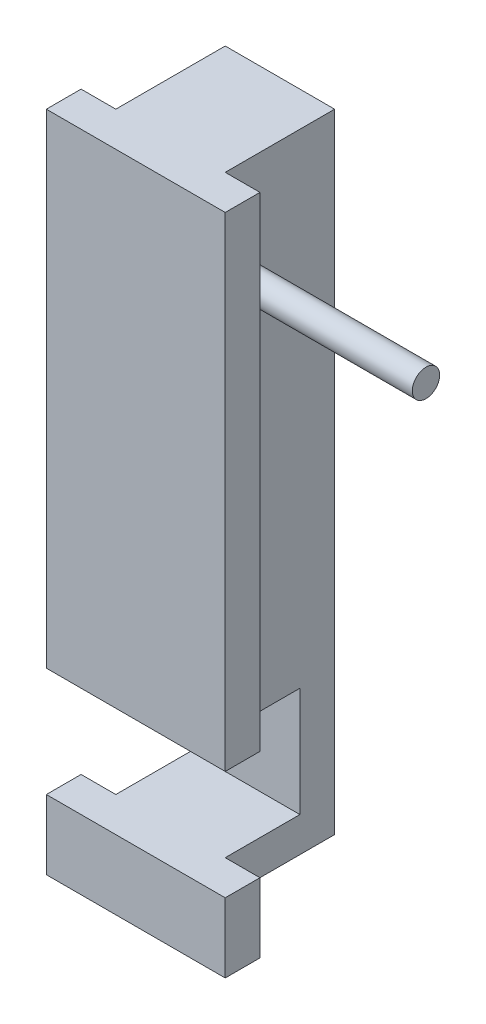
SolidWorks part; units mm, degrees
ref_plane "Front Plane" through (0, 0, 0) normal (0, 0, 1) x (1, 0, 0)
ref_plane "Top Plane" through (0, 0, 0) normal (0, 1, 0) x (1, 0, 0)
ref_plane "Right Plane" through (0, 0, 0) normal (1, 0, 0) x (0, 0, -1)
sketch "Sketch2" plane through (0, 0, 0) normal (1, 0, 0) x (0, 0, -1)
  line L0 (0, 0) -> (20, 0)
  line L1 (20, 0) -> (20, -20)
  line L2 (20, -20) -> (0, -20)
  line L3 (0, -20) -> (0, -32.7)
  line L4 (0, -32.7) -> (6.35, -32.7)
  line L5 (6.35, -32.7) -> (6.35, -26.35)
  line L6 (6.35, -26.35) -> (26.35, -26.35)
  line L7 (26.35, -26.35) -> (26.35, 88.5)
  line L8 (26.35, 88.5) -> (0, 88.5)
  line L9 (0, 88.5) -> (0, 0)
  dimension "D1" = 20
  dimension "D2" = 20
  dimension "D3" = 26.35
  dimension "D4" = 6.35
  dimension "D5" = 6.35
  dimension "D6" = 6.35
  dimension "D7" = 88.5
extrude "Boss-Extrude1" add sketch "Sketch2" along normal blind 32.7
sketch "Sketch3" plane through (0, 88.5, 0) normal (0, 1, 0) x (1, 0, 0)
  line L0 (0, 26.35) -> (6.35, 26.35)
  line L1 (32.7, 26.35) -> (0, 26.35) construction
  line L2 (6.35, 26.35) -> (6.35, 6.35)
  line L3 (6.35, 6.35) -> (0, 6.35)
  line L4 (0, 26.35) -> (0, 0) construction
  line L5 (0, 6.35) -> (0, 26.35)
  line L6 (32.7, 26.35) -> (32.7, 6.35)
  line L7 (32.7, 26.35) -> (32.7, 0) construction
  line L8 (32.7, 6.35) -> (26.35, 6.35)
  line L9 (26.35, 6.35) -> (26.35, 26.35)
  line L10 (26.35, 26.35) -> (32.7, 26.35)
  line L11 (32.7, 0) -> (0, 0) construction
  dimension "D1" = 6.35
  dimension "D2" = 6.35
  dimension "D3" = 6.35
  dimension "D4" = 6.35
extrude "Cut-Extrude2" cut sketch "Sketch3" against normal through all
sketch "Sketch4" plane through (26.35, 0, 0) normal (1, 0, 0) x (0, 0, -1)
  line L0 (0, 88.5) -> (0, 0) construction
  line L2 (26.35, -26.35) -> (26.35, 88.5) construction
  line L3 (20, 0) -> (6.35, 0) construction
  circle A0 centre (10, 69.86) radius 2.5
  dimension "D1" = 5
  dimension "D2" = 10
  dimension "D3" = 16.35
  dimension "D4" = 69.86
extrude "Boss-Extrude2" add sketch "Sketch4" along normal blind 33.05
